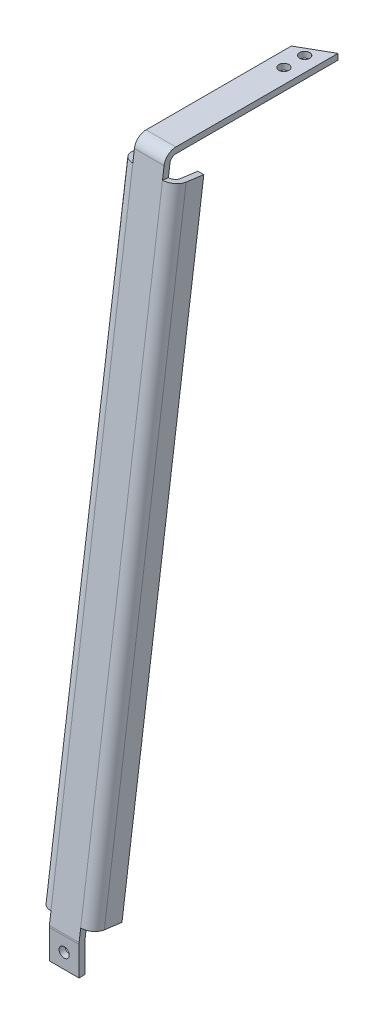
SolidWorks part; units mm, degrees
other "Roof Support Arm 1 Right"
ref_plane "Front Plane" through (0, 0, 0) normal (0, 0, 1) x (1, 0, 0)
ref_plane "Top Plane" through (0, 0, 0) normal (0, 1, 0) x (1, 0, 0)
ref_plane "Right Plane" through (0, 0, 0) normal (1, 0, 0) x (0, 0, -1)
sketch3d "Formed Web Section Sketch datum points"
  point P0 (-260, 0, 0)
  point P1 (-260, 10, 0)
  point P2 (-260, 0, 10)
ref_plane "Formed Web Section Sketch plane" through (-260, 0, 0) normal (1, 0, 0) x (0, 0, -1)
sketch "Formed Web Section Sketch" plane through (-260, 0, 0) normal (1, 0, 0) x (0, 0, -1)
  line L0 (-22, -64) -> (-77.3775, -64)
  line L1 (-81.3416, -67.4653) -> (-109.9641, -279.6667)
  line L2 (-110, -280.2014) -> (-110, -290)
  line L3 (-110, -290) -> (-108, -290)
  line L4 (-108, -290) -> (-108, -280.2014)
  line L5 (-107.9821, -279.9341) -> (-79.3595, -67.7327)
  line L6 (-77.3775, -66) -> (-22, -66)
  line L7 (-22, -66) -> (-22, -64)
  arc A0 (-77.3775, -64) -> (-81.3416, -67.4653) centre (-77.3775, -68) ccw
  arc A1 (-109.9641, -279.6667) -> (-110, -280.2014) centre (-106, -280.2014) ccw
  arc A2 (-107.9821, -279.9341) -> (-108, -280.2014) centre (-106, -280.2014) ccw
  arc A3 (-77.3775, -66) -> (-79.3595, -67.7327) centre (-77.3775, -68) ccw
extrude "Formed Web" add sketch "Formed Web Section Sketch" along normal blind 10 separate body
sketch3d "Edge Lip Sketch datum points"
  point P0 (-255, -71.5631, 80.8853)
  point P1 (-245, -71.5631, 80.8853)
  point P2 (-255, -70.2264, 90.7955)
ref_plane "Edge Lip Sketch plane" through (0, -80.9995, 10.9255) normal (0, -0.991, 0.1337) x (-1, 0, 0)
sketch "Edge Lip Sketch" plane through (0, -80.9995, 10.9255) normal (0, -0.991, 0.1337) x (-1, 0, 0)
  line L0 (264, -67.5933) -> (264, -61.5933)
  line L1 (264, -61.5933) -> (262, -61.5933)
  line L2 (262, -61.5933) -> (262, -67.5933)
  line L3 (260, -69.5933) -> (259.9, -69.5933)
  line L4 (259.9, -69.5933) -> (259.9, -71.5933)
  line L5 (259.9, -71.5933) -> (260, -71.5933)
  line L6 (246, -67.5933) -> (246, -61.5933)
  line L7 (246, -61.5933) -> (248, -61.5933)
  line L8 (248, -61.5933) -> (248, -67.5933)
  line L9 (250, -69.5933) -> (250.1, -69.5933)
  line L10 (250.1, -69.5933) -> (250.1, -71.5933)
  line L11 (250.1, -71.5933) -> (250, -71.5933)
  arc A0 (260, -71.5933) -> (264, -67.5933) centre (260, -67.5933) ccw
  arc A1 (260, -69.5933) -> (262, -67.5933) centre (260, -67.5933) ccw
  arc A2 (246, -67.5933) -> (250, -71.5933) centre (250, -67.5933) ccw
  arc A3 (248, -67.5933) -> (250, -69.5933) centre (250, -67.5933) ccw
extrude "Edge Stiffening Lips" add sketch "Edge Lip Sketch" along normal blind 206.1231
sketch3d "Wall Mount Hole Sketch datum points"
  point P0 (0, -63.8, 0)
  point P1 (10, -63.8, 0)
  point P2 (0, -63.8, 10)
ref_plane "Wall Mount Hole Sketch plane" through (0, -63.8, 0) normal (0, -1, 0) x (-1, 0, 0)
sketch "Wall Mount Hole Sketch" plane through (0, -63.8, 0) normal (0, -1, 0) x (-1, 0, 0)
  circle A0 centre (255, -29) radius 1.7
  circle A1 centre (255, -36) radius 1.7
extrude "Wall Mount Holes" cut sketch "Wall Mount Hole Sketch" along normal blind 2.4
sketch3d "Cover Mount Hole Sketch datum points"
  point P0 (0, 0, 107.8)
  point P1 (10, 0, 107.8)
  point P2 (0, 10, 107.8)
ref_plane "Cover Mount Hole Sketch plane" through (0, 0, 107.8) normal (0, 0, 1) x (1, 0, 0)
sketch "Cover Mount Hole Sketch" plane through (0, 0, 107.8) normal (0, 0, 1) x (1, 0, 0)
  circle A0 centre (-255, -285) radius 1.7
extrude "Cover Mount Hole" cut sketch "Cover Mount Hole Sketch" along normal blind 2.4
sketch3d "Lower Edge Clearance Sketch datum points"
  point P0 (0, -63.8, 0)
  point P1 (10, -63.8, 0)
  point P2 (0, -63.8, 10)
ref_plane "Lower Edge Clearance Sketch plane" through (0, -63.8, 0) normal (0, -1, 0) x (-1, 0, 0)
sketch "Lower Edge Clearance Sketch" plane through (0, -63.8, 0) normal (0, -1, 0) x (-1, 0, 0)
  line L0 (261, -20) -> (249, -20)
  line L1 (249, -20) -> (249, -22.23)
  line L2 (249, -22.23) -> (261, -29.07)
  line L3 (261, -29.07) -> (261, -20)
extrude "Lower Edge Clearance" cut sketch "Lower Edge Clearance Sketch" along normal blind 2.4
